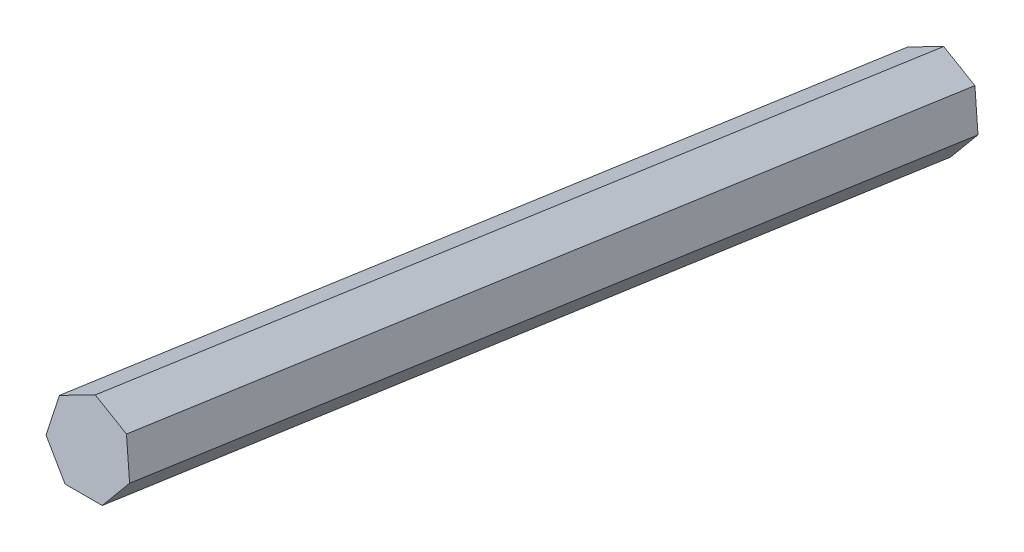
SolidWorks part; units mm, degrees
ref_plane "Front Plane" through (0, 0, 0) normal (0, 0, 1) x (1, 0, 0)
ref_plane "Top Plane" through (0, 0, 0) normal (0, 1, 0) x (1, 0, 0)
ref_plane "Right Plane" through (0, 0, 0) normal (1, 0, 0) x (0, 0, -1)
sketch "Sketch1" plane through (0, 0, 0) normal (1, 0, 0) x (0, 0, -1)
  line L0 (0, 0) -> (69.282, 0) construction
  line L1 (69.282, 0) -> (0, 10)
  line L2 (0, 0) -> (0, 31.9214) construction
  dimension "D1" = 70
  dimension "D2" = 10
ref_plane "Plane1" through (0, 0, -69.282) normal (0, 0.1429, 0.9897) x (1, 0, 0)
sketch "Sketch2" plane through (0, 0, -69.282) normal (0, 0.1429, 0.9897) x (1, 0, 0)
  line L15 (0, 3.5) -> (-2.7364, 2.1822)
  line L16 (-2.7364, 2.1822) -> (-3.4122, -0.7788)
  line L17 (-3.4122, -0.7788) -> (-1.5186, -3.1534)
  line L18 (-1.5186, -3.1534) -> (1.5186, -3.1534)
  line L19 (1.5186, -3.1534) -> (3.4122, -0.7788)
  line L20 (3.4122, -0.7788) -> (2.7364, 2.1822)
  line L21 (2.7364, 2.1822) -> (0, 3.5)
  circle A1 centre (0, 0) radius 3.5 construction
  point P1 (0, 0)
  dimension "D1" = 7
sweep "Sweep1" add profiles "Sketch2" path "Sketch1"
